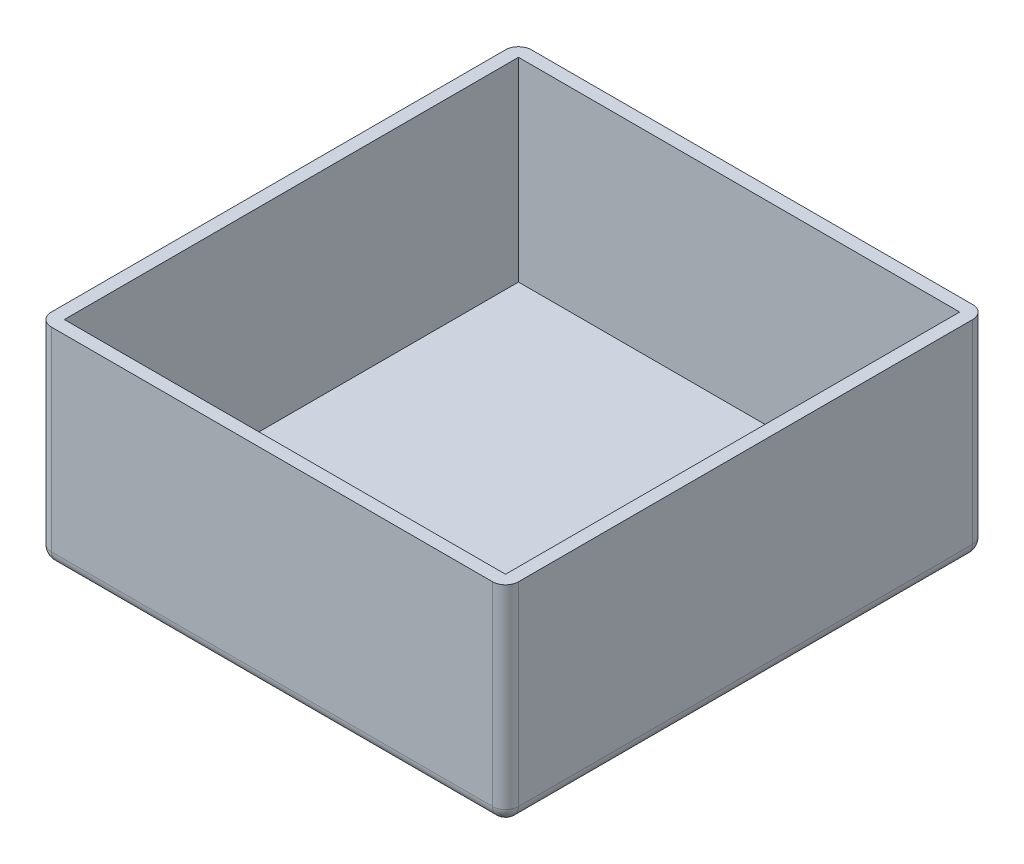
SolidWorks part; units mm, degrees
ref_plane "正面" through (0, 0, 0) normal (0, 0, 1) x (1, 0, 0)
ref_plane "平面" through (0, 0, 0) normal (0, 1, 0) x (1, 0, 0)
ref_plane "右側面" through (0, 0, 0) normal (1, 0, 0) x (0, 0, -1)
sketch "ｽｹｯﾁ1" plane through (0, 0, 0) normal (0, 1, 0) x (1, 0, 0)
  line L0 (-20.6822, 29.955) -> (15.3178, 29.955)
  line L1 (-20.6822, 29.955) -> (-20.6822, -7.045)
  line L2 (15.3178, 29.955) -> (15.3178, -7.045)
  line L3 (-20.6822, -7.045) -> (15.3178, -7.045)
  dimension "D1" = 37
  dimension "D2" = 36
extrude "ﾎﾞｽ - 押し出し2" add sketch "ｽｹｯﾁ1" along normal blind 16
sketch "ｽｹｯﾁ2" plane through (0, 16, 0) normal (0, 1, 0) x (1, 0, 0)
  line L3 (-19.6822, 28.955) -> (14.3178, 28.955)
  line L4 (-19.6822, 28.955) -> (-19.6822, -6.045)
  line L5 (14.3178, 28.955) -> (14.3178, -6.045)
  line L6 (-19.6822, -6.045) -> (14.3178, -6.045)
  dimension "D1" = 34
  dimension "D2" = 35
extrude "ｶｯﾄ - 押し出し1" cut sketch "ｽｹｯﾁ2" against normal blind 15
fillet "ﾌｨﾚｯﾄ1" radius 1 8 edges at (-2.6822, 0, -29.955) (-20.6822, 0, -11.455) (15.3178, 0, -11.455) (-2.6822, 0, 7.045) (15.3178, 8, 7.045) (-20.6822, 8, 7.045) (15.3178, 8, -29.955) (-20.6822, 8, -29.955)
